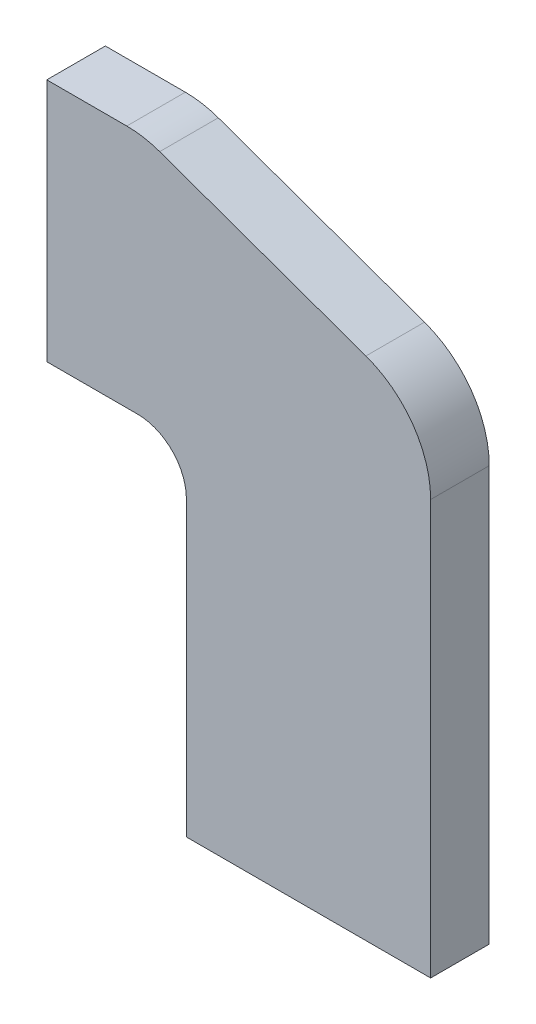
SolidWorks part; units mm, degrees
ref_plane "Спереди" through (0, 0, 0) normal (0, 0, 1) x (1, 0, 0)
ref_plane "Сверху" through (0, 0, 0) normal (0, 1, 0) x (1, 0, 0)
ref_plane "Справа" through (0, 0, 0) normal (1, 0, 0) x (0, 0, -1)
sketch "Эскиз1" plane through (0, 0, 0) normal (0, 0, 1) x (1, 0, 0)
  line L1 (0, 0) -> (78.62, 0)
  line L2 (0, 0) -> (0, 50)
  line L3 (0, 50) -> (78.62, 50)
  line L4 (78.62, 0) -> (78.62, 50)
  dimension "D1" = 78.62
  dimension "D2" = 50
extrude "Бобышка-Вытянуть1" add sketch "Эскиз1" along normal blind 12
sketch "Эскиз3" plane through (0, 0, 12) normal (0, 0, 1) x (1, 0, 0)
  line L0 (19.8589, 50) -> (78.62, 28.9521)
  line L5 (78.62, 0) -> (28.5958, 0)
  line L6 (78.62, 0) -> (78.62, 10)
  line L7 (78.62, 10) -> (28.5958, 10)
  line L8 (28.5958, 0) -> (28.5958, 10)
  line L9 (78.62, 50) -> (0, 50) construction
  line L10 (78.62, 0) -> (78.62, 50) construction
  line L11 (78.62, 28.9521) -> (78.62, 50)
  line L12 (78.62, 50) -> (19.8589, 50)
  dimension "D1" = 50.0242
  dimension "D2" = 10
extrude "Вырез-Вытянуть1" cut sketch "Эскиз3" against normal through all
fillet "Скругление3" radius 20 1 edges at (78.62, 28.9521, 6)
fillet "Скругление4" radius 20 1 edges at (19.8589, 50, 6)
sketch "Эскиз5" plane through (0, 0, 0) normal (-1, 0, 0) x (0, 0, 1)
  line L1 (0, 50) -> (0, 0) construction
  line L2 (12, 0) -> (0, 0) construction
  line L3 (12, 50) -> (0, 50) construction
  circle A0 centre (6, 7) radius 2.5
  circle A1 centre (6, 41) radius 2.5
  dimension "D1" = 5
  dimension "D2" = 6
  dimension "D3" = 34
  dimension "D4" = 7
  dimension "D5" = 9
extrude "Вырез-Вытянуть3" cut sketch "Эскиз5" against normal blind 20
sketch "Эскиз6" plane through (0, 0, 12) normal (0, 0, 1) x (1, 0, 0)
  line L1 (28.5958, 10) -> (78.62, 10)
  line L2 (28.5958, 10) -> (28.5958, -70)
  line L3 (28.5958, -70) -> (78.62, -70)
  line L4 (78.62, 10) -> (78.62, -70)
  dimension "D1" = 80
extrude "Бобышка-Вытянуть2" add sketch "Эскиз6" against normal up to surface (12 mm away) up to face at (35.8158, 24.4211, 0)
fillet "Скругление5" radius 10 1 edges at (28.5958, 0, 6)
sketch "Эскиз7" plane through (0, -70, 0) normal (0, -1, 0) x (1, 0, 0)
  line L0 (28.5958, 0) -> (28.5958, 12) construction
  circle A0 centre (38.5958, 6) radius 2.5
  circle A1 centre (68.5958, 6) radius 2.5
  point P4 (28.5958, 6)
  dimension "D1" = 5
  dimension "D2" = 0
  dimension "D3" = 10
  dimension "D4" = 2
extrude "Вырез-Вытянуть4" cut sketch "Эскиз7" against normal blind 30
